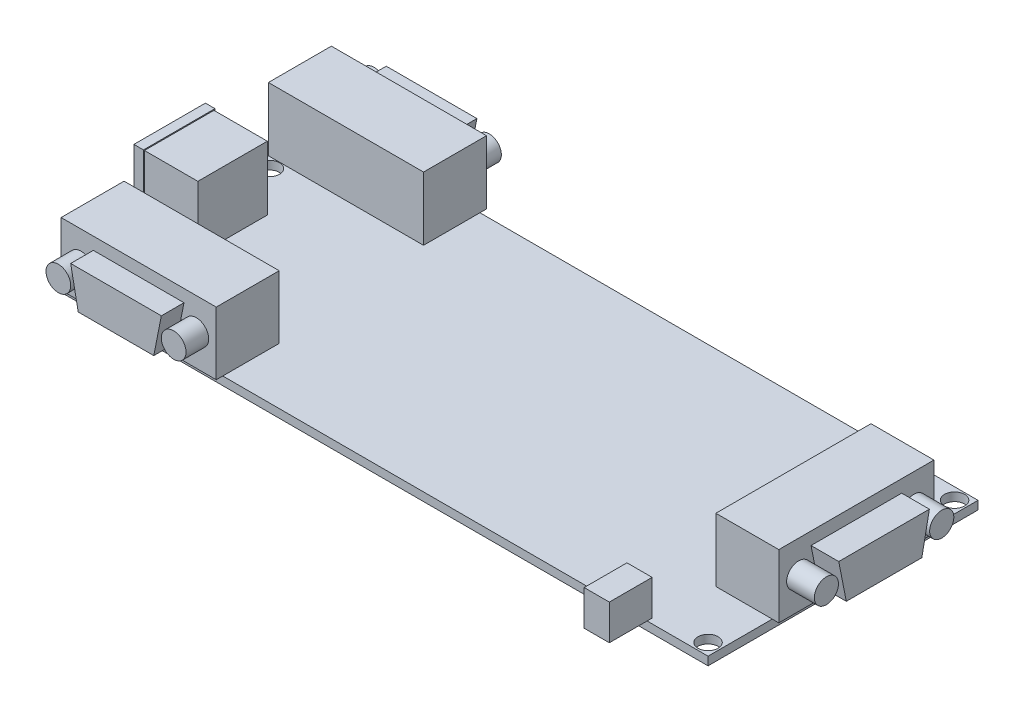
SolidWorks part; units mm, degrees
ref_plane "Front Plane" through (0, 0, 0) normal (0, 0, 1) x (1, 0, 0)
ref_plane "Top Plane" through (0, 0, 0) normal (0, 1, 0) x (1, 0, 0)
ref_plane "Right Plane" through (0, 0, 0) normal (1, 0, 0) x (0, 0, -1)
sketch "Sketch1" plane through (0, 0, 0) normal (0, 1, 0) x (1, 0, 0)
  line L1 (-64.85, -26.8) -> (64.85, -26.8)
  line L2 (-64.85, -26.8) -> (-64.85, 26.8)
  line L3 (-64.85, 26.8) -> (64.85, 26.8)
  line L4 (64.85, -26.8) -> (64.85, 26.8)
  line L5 (-64.85, -26.8) -> (64.85, 26.8) construction
  line L6 (-64.85, 26.8) -> (64.85, -26.8) construction
  point P0 (0, 0)
  dimension "D1" = 129.7
  dimension "D2" = 53.6
extrude "BoardBase" add sketch "Sketch1" along normal blind 1.67
sketch "Sketch3" plane through (0, 1.67, 0) normal (0, 1, 0) x (1, 0, 0)
  line L0 (-64.85, -26.8) -> (64.85, -26.8) construction
  line L1 (53.65, 16.75) -> (66.15, 16.75)
  line L2 (53.65, 16.75) -> (53.65, -14.05)
  line L3 (53.65, -14.05) -> (66.15, -14.05)
  line L4 (66.15, 16.75) -> (66.15, -14.05)
  line L5 (53.65, 16.75) -> (66.15, -14.05) construction
  line L6 (53.65, -14.05) -> (66.15, 16.75) construction
  line L7 (64.85, -26.8) -> (64.85, 26.8) construction
  point P0 (59.9, 1.35)
  dimension "D1" = 30.8
  dimension "D2" = 12.5
  dimension "D3" = 12.75
  dimension "D4" = 11.2
extrude "Boss-Extrude2" add sketch "Sketch3" along normal blind 12.6
sketch "Sketch4" plane through (66.15, 0, 0) normal (1, 0, 0) x (0, 0, -1)
  line L0 (-14.05, 7.97) -> (16.75, 7.97) construction
  line L1 (-14.05, 14.27) -> (-14.05, 1.67) construction
  line L2 (16.75, 14.27) -> (16.75, 1.67) construction
  line L3 (1.35, 14.27) -> (1.35, 1.67) construction
  line L4 (-14.05, 14.27) -> (16.75, 14.27) construction
  line L5 (-14.05, 1.67) -> (16.75, 1.67) construction
  line L6 (-7.65, 11.77) -> (10.35, 11.77)
  line L7 (10.35, 11.77) -> (8.85, 4.17)
  line L8 (8.85, 4.17) -> (-6.15, 4.17)
  line L9 (-6.15, 4.17) -> (-7.65, 11.77)
  circle A0 centre (-10.1, 7.97) radius 2.4
  circle A1 centre (12.8, 7.97) radius 2.4
  dimension "D1" = 22.9
  dimension "D2" = 4.8
  dimension "D3" = 18
  dimension "D4" = 15
  dimension "D5" = 3.8
  dimension "D6" = 3.8
extrude "Boss-Extrude3" add sketch "Sketch4" along normal blind 5.5
sketch "Sketch6" plane through (0, 1.67, 0) normal (0, 1, 0) x (1, 0, 0)
  line L0 (-64.85, -26.8) -> (64.85, -26.8) construction
  line L1 (-31.5, -15.6) -> (-62.3, -15.6)
  line L2 (-31.5, -15.6) -> (-31.5, -28.1)
  line L3 (-31.5, -28.1) -> (-62.3, -28.1)
  line L4 (-62.3, -15.6) -> (-62.3, -28.1)
  line L5 (-31.5, -15.6) -> (-62.3, -28.1) construction
  line L6 (-31.5, -28.1) -> (-62.3, -15.6) construction
  line L7 (-64.85, 26.8) -> (-64.85, -26.8) construction
  point P0 (-46.9, -21.85)
  dimension "D1" = 12.5
  dimension "D2" = 30.8
  dimension "D3" = 11.2
  dimension "D4" = 2.55
extrude "Boss-Extrude5" add sketch "Sketch6" along normal blind 12.5
sketch "Sketch7" plane through (0, 0, 28.1) normal (0, 0, 1) x (1, 0, 0)
  line L0 (-62.3, 7.92) -> (-31.5, 7.92) construction
  line L1 (-62.3, 14.17) -> (-62.3, 1.67) construction
  line L2 (-31.5, 14.17) -> (-31.5, 1.67) construction
  line L3 (-46.9, 14.17) -> (-46.9, 1.67) construction
  line L4 (-62.3, 14.17) -> (-31.5, 14.17) construction
  line L5 (-62.3, 1.67) -> (-31.5, 1.67) construction
  line L6 (-55.9, 11.72) -> (-37.9, 11.72)
  line L7 (-37.9, 11.72) -> (-39.4, 4.12)
  line L8 (-39.4, 4.12) -> (-54.4, 4.12)
  line L9 (-54.4, 4.12) -> (-55.9, 11.72)
  circle A0 centre (-58.35, 7.92) radius 2.45
  circle A1 centre (-35.45, 7.92) radius 2.45
  dimension "D1" = 4.9
  dimension "D2" = 22.9
  dimension "D3" = 15
  dimension "D4" = 18
  dimension "D5" = 3.8
  dimension "D6" = 3.8
extrude "Boss-Extrude6" add sketch "Sketch7" along normal blind 4.5
sketch "Sketch5" plane through (0, 1.67, 0) normal (0, 1, 0) x (1, 0, 0)
  line L0 (64.85, 26.8) -> (-64.85, 26.8) construction
  line L1 (-64.84, 15.6) -> (-34.04, 15.6)
  line L2 (-64.84, 15.6) -> (-64.84, 28.1)
  line L3 (-64.84, 28.1) -> (-34.04, 28.1)
  line L4 (-34.04, 15.6) -> (-34.04, 28.1)
  line L5 (-64.84, 15.6) -> (-34.04, 28.1) construction
  line L6 (-64.84, 28.1) -> (-34.04, 15.6) construction
  line L7 (-64.85, 26.8) -> (-64.85, -26.8) construction
  point P2 (-49.44, 21.85)
  dimension "D1" = 12.5
  dimension "D2" = 11.2
  dimension "D3" = 30.8
  dimension "D4" = 0.01
extrude "Boss-Extrude4" add sketch "Sketch5" along normal blind 12.6
sketch "Sketch9" plane through (0, 0, -28.1) normal (0, 0, -1) x (-1, 0, 0)
  line L0 (34.04, 7.97) -> (64.84, 7.97) construction
  line L1 (49.44, 14.27) -> (49.44, 1.67) construction
  line L2 (40.44, 11.77) -> (58.44, 11.77)
  line L3 (58.44, 11.77) -> (56.94, 4.17)
  line L4 (56.94, 4.17) -> (41.94, 4.17)
  line L5 (41.94, 4.17) -> (40.44, 11.77)
  line L6 (34.04, 1.67) -> (64.84, 1.67) construction
  line L7 (34.04, 14.27) -> (64.84, 14.27) construction
  line L8 (34.04, 14.27) -> (34.04, 1.67) construction
  line L9 (64.84, 14.27) -> (64.84, 1.67) construction
  circle A0 centre (37.99, 7.97) radius 2.4
  circle A1 centre (60.89, 7.97) radius 2.4
  dimension "D1" = 4.8
  dimension "D6" = 22.9
  dimension "D2" = 15
  dimension "D3" = 18
  dimension "D4" = 3.8
  dimension "D5" = 3.8
extrude "Boss-Extrude7" add sketch "Sketch9" along normal blind 4.5
sketch "Sketch10" plane through (0, 1.67, 0) normal (0, 1, 0) x (1, 0, 0)
  line L0 (-64.85, 26.8) -> (-64.85, -26.8) construction
  line L1 (-65.35, -8.5) -> (-54.75, -8.5)
  line L2 (-65.35, -8.5) -> (-65.35, 5.3)
  line L3 (-65.35, 5.3) -> (-54.75, 5.3)
  line L4 (-54.75, -8.5) -> (-54.75, 5.3)
  line L5 (-65.35, -8.5) -> (-54.75, 5.3) construction
  line L6 (-65.35, 5.3) -> (-54.75, -8.5) construction
  line L7 (-64.85, -26.8) -> (-62.3, -26.8) construction
  point P0 (-60.05, -1.6)
  point P7 (-63.575, -26.8)
  dimension "D1" = 13.8
  dimension "D2" = 10.6
  dimension "D3" = 10.1
  dimension "D4" = 18.3
extrude "Boss-Extrude8" add sketch "Sketch10" along normal blind 12.7
sketch "Sketch12" plane through (-65.35, 0, 0) normal (-1, 0, 0) x (0, 0, 1)
  line L0 (8.7, 14.57) -> (-5.5, 14.57)
  line L1 (-5.5, 14.57) -> (-5.5, 1.47)
  line L2 (-5.5, 1.47) -> (8.7, 1.47)
  line L3 (8.7, 1.47) -> (8.7, 14.57)
  line L4 (-5.3, 1.67) -> (8.5, 1.67)
  line L5 (8.5, 1.67) -> (8.5, 14.37)
  line L6 (8.5, 14.37) -> (-5.3, 14.37)
  line L7 (-5.3, 14.37) -> (-5.3, 1.67)
  line L8 (-5.3, 1.67) -> (8.5, 1.67) construction
  line L9 (8.5, 1.67) -> (8.5, 14.37) construction
  line L10 (8.5, 14.37) -> (-5.3, 14.37) construction
  line L11 (-5.3, 14.37) -> (-5.3, 1.67) construction
  dimension "D1" = 0
  dimension "D2" = 0.2
extrude "Boss-Extrude9" add sketch "Sketch12" along normal blind 1.9
sketch "Sketch13" plane through (0, 0, 0) normal (0, -1, 0) x (1, 0, 0)
  line L1 (43.15, 20.5) -> (48.35, 20.5)
  line L2 (43.15, 20.5) -> (43.15, -25.8)
  line L3 (43.15, -25.8) -> (48.35, -25.8)
  line L4 (48.35, 20.5) -> (48.35, -25.8)
  line L5 (43.15, 20.5) -> (48.35, -25.8) construction
  line L6 (43.15, -25.8) -> (48.35, 20.5) construction
  line L7 (-64.85, 26.8) -> (64.85, 26.8) construction
  line L8 (64.85, -26.8) -> (-64.85, -26.8) construction
  line L9 (64.85, 26.8) -> (64.85, -26.8) construction
  point P0 (45.75, -2.65)
  dimension "D1" = 16.5
  dimension "D2" = 6.3
  dimension "D3" = 1
  dimension "D4" = 5.2
extrude "MolexHeader" add sketch "Sketch13" along normal blind 2.7
sketch "Sketch14" plane through (0, 1.67, 0) normal (0, 1, 0) x (1, 0, 0)
  line L0 (64.85, 16.75) -> (64.85, 26.8) construction
  line L1 (64.85, 26.8) -> (-34.04, 26.8) construction
  line L2 (64.85, -26.8) -> (64.85, -14.05) construction
  line L3 (-31.5, -26.8) -> (64.85, -26.8) construction
  line L4 (-64.85, -26.8) -> (-62.3, -26.8) construction
  line L5 (-64.85, -8.5) -> (-64.85, -26.8) construction
  line L6 (-64.85, 26.8) -> (-64.85, 5.3) construction
  circle A0 centre (62.5, 24.5) radius 2
  circle A1 centre (62.5, -24.45) radius 2
  circle A2 centre (-62.55, -12.9) radius 2
  circle A3 centre (-62.55, 13.5) radius 2
  dimension "D1" = 4
  dimension "D5" = 2.35
  dimension "D8" = 2.3
  dimension "D9" = 13.3
  dimension "D2" = 2.35
  dimension "D3" = 2.3
  dimension "D4" = 2.35
  dimension "D6" = 13.9
  dimension "D7" = 2.3
extrude "MountHoles" cut sketch "Sketch14" against normal through all
sketch "Sketch15" plane through (0, 1.67, 0) normal (0, 1, 0) x (1, 0, 0)
  line L0 (64.85, -26.8) -> (64.85, -14.05) construction
  line L1 (47.75, -25.8) -> (52.75, -25.8)
  line L2 (47.75, -25.8) -> (47.75, -34.3)
  line L3 (47.75, -34.3) -> (52.75, -34.3)
  line L4 (52.75, -25.8) -> (52.75, -34.3)
  line L5 (-31.5, -26.8) -> (64.85, -26.8) construction
  dimension "D1" = 5
  dimension "D2" = 8.5
  dimension "D3" = 12.1
  dimension "D4" = 1
extrude "StimHeader" add sketch "Sketch15" along normal blind 7
